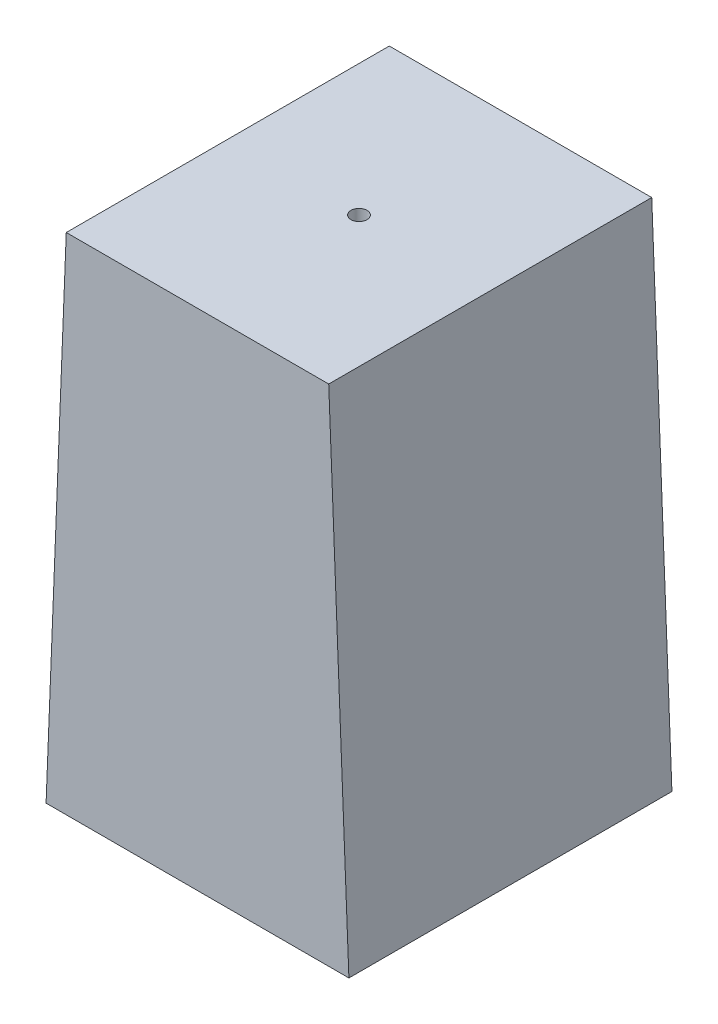
SolidWorks part; units mm, degrees
ref_plane "Front Plane" through (0, 0, 0) normal (0, 0, 1) x (1, 0, 0)
ref_plane "Top Plane" through (0, 0, 0) normal (0, 1, 0) x (1, 0, 0)
ref_plane "Right Plane" through (0, 0, 0) normal (1, 0, 0) x (0, 0, -1)
sketch "Sketch1" plane through (0, 0, 0) normal (0, 0, 1) x (1, 0, 0)
  line L0 (0, 0) -> (15, 0)
  line L1 (0, 0) -> (1, 24.98)
  line L2 (1, 24.98) -> (14, 24.98)
  line L3 (15, 0) -> (14, 24.98)
  point P5 (7.5, 24.98)
  point P6 (7.5, 0)
  dimension "D1" = 25
  dimension "D2" = 15
  dimension "D3" = 13
extrude "Boss-Extrude1" add sketch "Sketch1" along normal blind 16 contours L3 L2 L1 L0
sketch "Sketch4" plane through (0, 24.98, 0) normal (0, 1, 0) x (1, 0, 0)
  line L0 (1, 0) -> (14, -16) construction
  circle A0 centre (7.5, -8) radius 0.4
extrude "Cut-Extrude1" cut sketch "Sketch4" against normal blind 32
